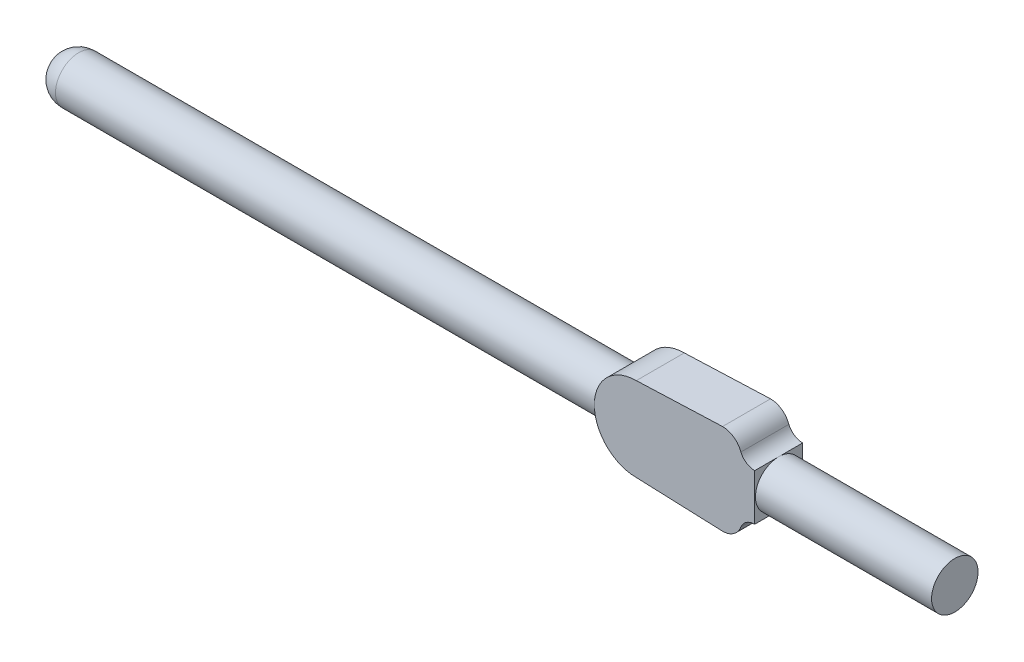
SolidWorks part; units mm, degrees
ref_plane "Alzado" through (0, 0, 0) normal (0, 0, 1) x (1, 0, 0)
ref_plane "Planta" through (0, 0, 0) normal (0, 1, 0) x (1, 0, 0)
ref_plane "Vista lateral" through (0, 0, 0) normal (1, 0, 0) x (0, 0, -1)
sketch "Croquis1" plane through (0, 0, 0) normal (0, 0, 1) x (1, 0, 0)
  line L0 (0, 359.1368) -> (0, -481.9187) construction
  line L1 (-657.792, 0) -> (755.6133, 0) construction
  line L3 (-300, 0) -> (300, 0)
  line L5 (-284.5, 15.5) -> (300, 15.5)
  line L6 (300, 0) -> (300, 15.5)
  arc A2 (-300, 0) -> (-284.5, 15.5) centre (-284.5, 0) cw
  point P9 (0, 0)
  dimension "D3" = 600
  dimension "D2" = 300
  dimension "D1" = 15.5
revolve "Revolución1" add sketch "Croquis1" angle 360 about L1
sketch "Croquis3" plane through (0, 0, 0) normal (0, 0, 1) x (1, 0, 0)
  line L0 (75.5, 87.2879) -> (75.5, -75.7996) construction
  line L1 (-284.5, 15.5) -> (-284.5, -15.5) construction
  line L2 (182.5, 79.0968) -> (182.5, -79.9585) construction
  line L3 (275.34, 0) -> (-79.3359, 0) construction
  line L4 (161.0396, 30.25) -> (161.0396, -30.25) construction
  line L5 (103.5, 28) -> (103.5, -28) construction
  line L7 (103.5, -28) -> (161.0396, -30.25)
  line L8 (103.5, 28) -> (161.0396, 30.25)
  line L9 (-284.5, -15.5) -> (300, -15.5) construction
  line L10 (-284.5, -15.5) -> (300, -15.5)
  line L11 (182.5, 15.5) -> (182.5, -15.5)
  arc A0 (173.2816, -21.6243) -> (182.5, -15.5) centre (182.5, -25.5) cw
  arc A1 (161.0396, -30.25) -> (173.2816, -21.6243) centre (161.0396, -17.25) ccw
  arc A2 (103.5, -28) -> (103.5, 28) centre (103.5, 0) cw
  arc A3 (173.2816, 21.6243) -> (182.5, 15.5) centre (182.5, 25.5) ccw
  arc A4 (161.0396, 30.25) -> (173.2816, 21.6243) centre (161.0396, 17.25) cw
  point P11 (161.0396, 0)
  point P14 (103.5, 0)
  dimension "D5" = 10
  dimension "D6" = 13
  dimension "D8" = 28
  dimension "D1" = 360
  dimension "D2" = 107
  dimension "D3" = 56
  dimension "D4" = 60.5
  dimension "D7" = 21.4604
extrude "Saliente-Extruir1" add sketch "Croquis3" along normal mid plane 32 contours A4 L8 A2 L10 L11 A3 | A2 L7 A1 A0 L10
